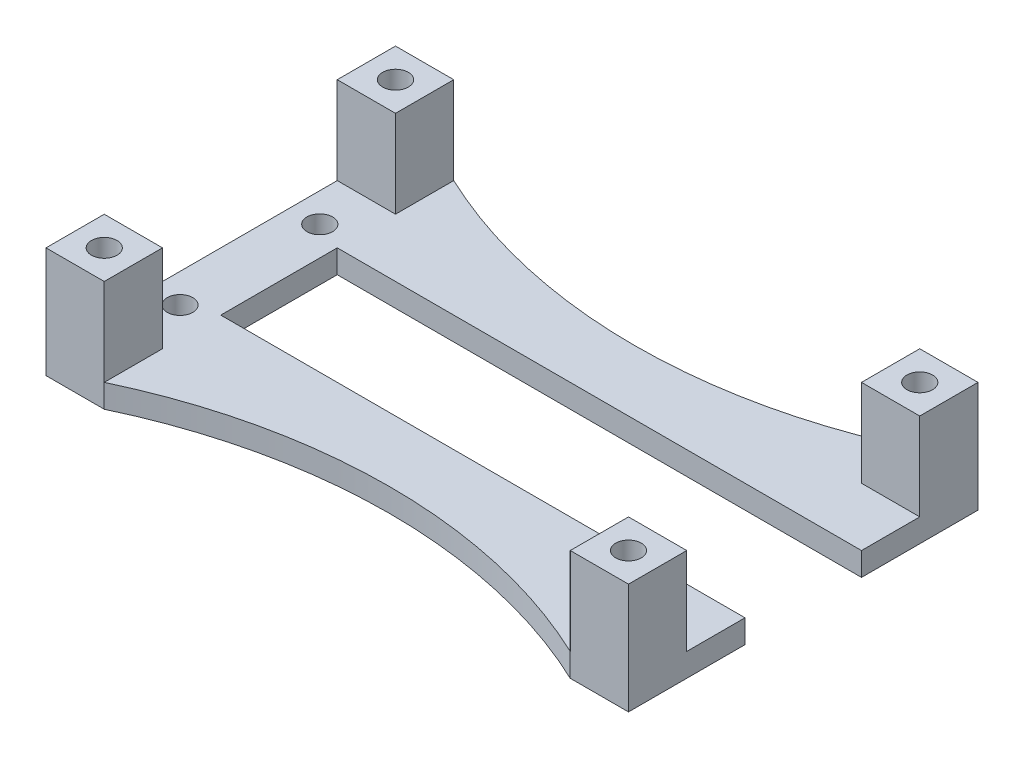
SolidWorks part; units mm, degrees
ref_plane "Front Plane" through (0, 0, 0) normal (0, 0, 1) x (1, 0, 0)
ref_plane "Top Plane" through (0, 0, 0) normal (0, 1, 0) x (1, 0, 0)
ref_plane "Right Plane" through (0, 0, 0) normal (1, 0, 0) x (0, 0, -1)
sketch "Sketch1" plane through (0, 0, 0) normal (0, 1, 0) x (1, 0, 0)
  line L0 (10, 10) -> (10, -10)
  line L1 (0, -20) -> (100, -20)
  line L2 (0, -20) -> (0, 20)
  line L3 (0, 20) -> (100, 20)
  line L4 (100, -20) -> (100, 20) construction
  line L5 (10, -10) -> (90, -10)
  line L6 (90, -10) -> (90, 10) construction
  line L7 (90, 10) -> (10, 10)
  line L8 (90, 10) -> (100, 10)
  line L11 (100, 10) -> (100, 20)
  line L13 (50, -20) -> (50, -10) construction
  line L14 (50, 10) -> (50, 20) construction
  line L16 (90, -10) -> (100, -10)
  line L17 (100, -20) -> (100, -10)
  line L18 (100, -20) -> (100, -30)
  line L19 (100, -30) -> (90, -30)
  line L20 (90, -30) -> (90, -20) construction
  line L21 (100, 20) -> (100, 30)
  line L22 (100, 30) -> (90, 30)
  line L23 (90, 30) -> (90, 20) construction
  line L24 (0, -20) -> (0, -30)
  line L25 (0, -30) -> (10, -30)
  line L26 (10, -30) -> (10, -20) construction
  line L27 (0, 20) -> (0, 30)
  line L28 (0, 30) -> (10, 30)
  line L29 (10, 30) -> (10, 20) construction
  line L30 (-55, 0) -> (55, 0) construction
  line L31 (0, 0) -> (100, 0) construction
  circle A7 centre (5, 25) radius 2.2
  arc A26 (90, -30) -> (10, -30) centre (50, -114.3889) ccw
  arc A27 (10, 30) -> (90, 30) centre (50, 114.3889) ccw
  circle A28 centre (5, -12) radius 2.2
  circle A29 centre (5, -25) radius 2.2
  circle A46 centre (95, 25) radius 2.2
  circle A47 centre (95, -25) radius 2.2
  circle A48 centre (5, 12) radius 2.2
  point P33 (50, 21)
  point P34 (50, -21)
  point P39 (0, 0)
  dimension "D25" = 4.4
  dimension "D4" = 4.4
  dimension "D18" = 4.4
  dimension "D19" = 4.4
  dimension "D1" = 40
  dimension "D2" = 100
  dimension "D3" = 10
  dimension "D22" = 10
  dimension "D23" = 10
  dimension "D24" = 10
  dimension "D6" = 5
  dimension "D8" = 5
  dimension "D13" = 5
  dimension "D16" = 5
  dimension "D7" = 10
  dimension "D10" = 10
  dimension "D11" = 10
  dimension "D12" = 10
  dimension "D9" = 5
  dimension "D14" = 5
  dimension "D15" = 10
  dimension "D17" = 10
  dimension "D20" = 10
  dimension "D21" = 10
  dimension "D5" = 5
  dimension "D26" = 5
  dimension "D27" = 1
  dimension "D28" = 1
  dimension "D29" = 5
  dimension "D30" = 12
extrude "Extrude-Body" add sketch "Sketch1" along normal blind 4
sketch "Sketch5" plane through (0, 4, 0) normal (0, 1, 0) x (1, 0, 0)
  line L9 (90, -20) -> (100, -20)
  line L21 (100, -20) -> (100, -30)
  line L36 (100, -30) -> (90, -30)
  line L37 (90, -30) -> (90, -20)
  line L38 (100, 20) -> (100, 30)
  line L39 (100, 30) -> (90, 30)
  line L41 (90, 30) -> (90, 20)
  line L42 (90, 20) -> (100, 20)
  line L43 (10, 20) -> (10, 30)
  line L44 (10, 30) -> (0, 30)
  line L46 (0, 30) -> (0, 20)
  line L47 (0, -30) -> (0, 30) construction
  line L48 (0, 20) -> (10, 20)
  line L49 (10, -20) -> (0, -20)
  line L50 (0, -20) -> (0, -30)
  line L51 (0, -30) -> (10, -30)
  line L52 (10, -30) -> (10, -20)
  circle A0 centre (95, 25) radius 2.2
  circle A3 centre (95, -25) radius 2.2
  circle A5 centre (5, -25) radius 2.2
  circle A8 centre (5, 25) radius 2.2
  circle A9 centre (5, -25) radius 2.2 construction
  circle A10 centre (5, 25) radius 2.2 construction
  circle A11 centre (95, 25) radius 2.2 construction
  circle A12 centre (95, -25) radius 2.2 construction
  point P9 (0, 0)
  dimension "D1" = 10
  dimension "D2" = 10
  dimension "D3" = 10
  dimension "D4" = 10
  dimension "D5" = 10
  dimension "D6" = 10
  dimension "D7" = 10
  dimension "D8" = 10
extrude "Extrude-Legs" add sketch "Sketch5" along normal blind 15
sketch "Sketch6" plane through (0, 0, 0) normal (0, -1, 0) x (1, 0, 0)
  circle A0 centre (5, -25) radius 4.215
  circle A2 centre (5, 25) radius 4.215
  circle A3 centre (95, 25) radius 4.215
  circle A5 centre (95, -25) radius 4.215
  dimension "D1" = 8.43
  dimension "D3" = 8.43
  dimension "D4" = 8.43
  dimension "D6" = 8.43
extrude "Cut-Bolt Head Insets" cut sketch "Sketch6" against normal blind 2.5
equation "\"boltdiameter\"=4.4"
equation "\"D25@Sketch1\"=\"boltdiameter\""
equation "\"D4@Sketch1\"=\"boltdiameter\""
equation "\"D18@Sketch1\"=\"boltdiameter\""
equation "\"D19@Sketch1\"=\"boltdiameter\""
equation "\"boltfacediameter\"=7"
equation "\"insetNutFlat\"=8.4"
equation "\"screwInset\"=8.43"
equation "\"D1@Sketch6\"=\"screwInset\""
equation "\"D3@Sketch6\"=\"screwInset\""
equation "\"D4@Sketch6\"=\"screwInset\""
equation "\"D6@Sketch6\"=\"screwInset\""
equation "\"slotLength\"=80"
